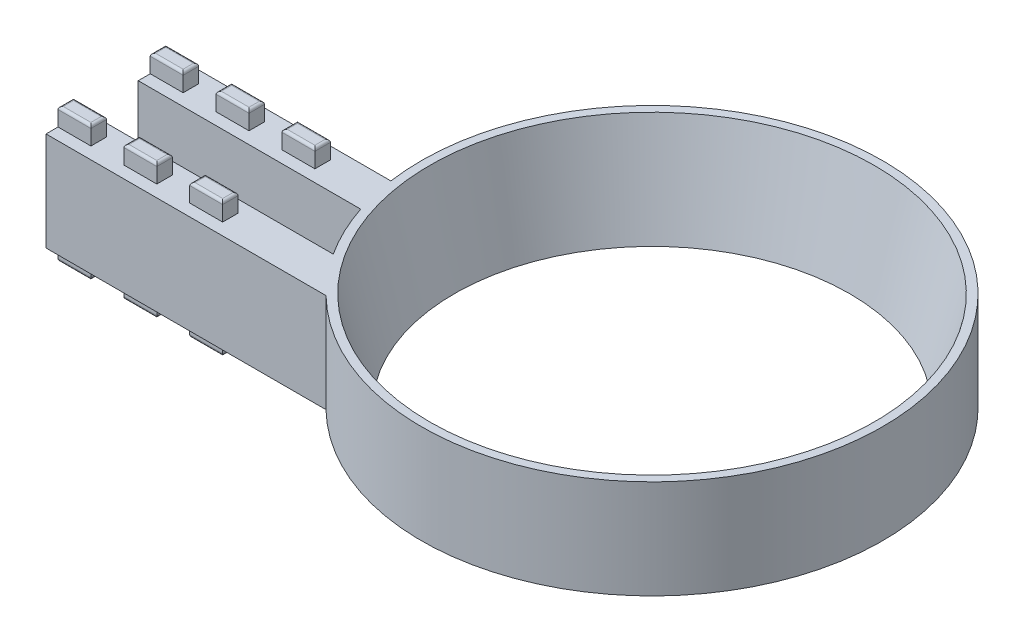
SolidWorks part; units mm, degrees
ref_plane "Front Plane" through (0, 0, 0) normal (0, 0, 1) x (1, 0, 0)
ref_plane "Top Plane" through (0, 0, 0) normal (0, 1, 0) x (1, 0, 0)
ref_plane "Right Plane" through (0, 0, 0) normal (1, 0, 0) x (0, 0, -1)
sketch "Sketch1" plane through (0, 0, 0) normal (0, 1, 0) x (1, 0, 0)
  line L0 (0, 0) -> (-44.45, 0) construction
  circle A0 centre (0, 0) radius 44.45
  dimension "D1" = 88.9
extrude "Boss-Extrude1" add sketch "Sketch1" along normal blind 19.05 contours A0
sketch "Sketch3" plane through (0, 0, 0) normal (0, -1, 0) x (1, 0, 0)
  line L0 (0, 0) -> (-44.45, 0) construction
  line L1 (-31.1085, 31.75) -> (-85.09, 31.75)
  line L2 (-85.09, 31.75) -> (-85.09, 6.35)
  line L3 (-85.09, 6.35) -> (-43.9941, 6.35)
  circle A0 centre (0, 0) radius 44.45 construction
  arc A1 (-43.9941, 6.35) -> (-31.1085, 31.75) centre (0, 0) cw
  dimension "D1" = 25.4
  dimension "D2" = 40.64
  dimension "D3" = 31.75
extrude "Boss-Extrude2" add sketch "Sketch3" against normal blind 3.175 contours L3 A1 L1 L2
sketch "Sketch4" plane through (0, 0, 31.75) normal (0, 0, 1) x (1, 0, 0)
  line L0 (-85.09, 3.175) -> (-85.09, 19.05)
  line L1 (-85.09, 19.05) -> (-31.1085, 19.05)
  line L2 (44.45, 19.05) -> (-44.45, 19.05) construction
  line L3 (-31.1085, 19.05) -> (-31.1085, 3.175)
  line L4 (-31.1085, 3.175) -> (-85.09, 3.175) construction
  line L5 (-31.1085, 3.175) -> (-85.09, 3.175)
  line L6 (-31.1085, 3.175) -> (-43.9941, 3.175) construction
  line L7 (-31.1085, 3.175) -> (-31.1085, 0) construction
sketch "Sketch5" plane through (0, 0, 6.35) normal (0, 0, -1) x (-1, 0, 0)
  line L0 (85.09, 3.175) -> (85.09, 19.05)
  line L1 (85.09, 19.05) -> (31.1085, 19.05)
  line L2 (31.1085, 19.05) -> (31.1085, 3.175)
  line L3 (31.1085, 3.175) -> (85.09, 3.175)
  line L4 (44.45, 19.05) -> (-44.45, 19.05) construction
extrude "Boss-Extrude3" add sketch "Sketch4" against normal blind 7.62
extrude "Boss-Extrude4" add sketch "Sketch5" against normal blind 7.62
sketch "Sketch2" plane through (0, 0, 0) normal (0, -1, 0) x (1, 0, 0)
  circle A0 centre (0, 0) radius 38.1
  dimension "D1" = 76.2
extrude "Cut-Extrude1" cut sketch "Sketch2" against normal through all draft 14 draft outward yes
ref_plane "Plane1" through (0, 0, 19.05) normal (0, 0, 1) x (1, 0, 0)
ref_plane "Plane2" through (0, 9.525, 0) normal (0, 1, 0) x (1, 0, 0)
sketch "Sketch6" plane through (0, 19.05, 0) normal (0, 1, 0) x (1, 0, 0)
  line L0 (-85.09, -24.13) -> (-85.09, -31.75) construction
  line L1 (-85.09, -29.4386) -> (-78.74, -29.4386)
  line L2 (-85.09, -29.4386) -> (-85.09, -26.4414)
  line L3 (-85.09, -26.4414) -> (-78.74, -26.4414)
  line L4 (-78.74, -29.4386) -> (-78.74, -26.4414)
  line L5 (-72.39, -29.4386) -> (-72.39, -26.4414)
  line L6 (-72.39, -29.4386) -> (-66.04, -29.4386)
  line L7 (-66.04, -29.4386) -> (-66.04, -26.4414)
  line L8 (-72.39, -26.4414) -> (-66.04, -26.4414)
  line L9 (-59.69, -29.4386) -> (-59.69, -26.4414)
  line L10 (-59.69, -29.4386) -> (-53.34, -29.4386)
  line L11 (-53.34, -29.4386) -> (-53.34, -26.4414)
  line L12 (-59.69, -26.4414) -> (-53.34, -26.4414)
  line L13 (-8.7312, -19.05) -> (8.7312, -19.05) construction
  line L14 (-59.69, -8.6614) -> (-53.34, -8.6614)
  line L15 (-53.34, -8.6614) -> (-53.34, -11.6586)
  line L16 (-59.69, -11.6586) -> (-53.34, -11.6586)
  line L17 (-59.69, -8.6614) -> (-59.69, -11.6586)
  line L18 (-72.39, -8.6614) -> (-66.04, -8.6614)
  line L19 (-66.04, -8.6614) -> (-66.04, -11.6586)
  line L20 (-72.39, -11.6586) -> (-66.04, -11.6586)
  line L21 (-72.39, -8.6614) -> (-72.39, -11.6586)
  line L22 (-85.09, -11.6586) -> (-78.74, -11.6586)
  line L23 (-78.74, -8.6614) -> (-78.74, -11.6586)
  line L24 (-85.09, -8.6614) -> (-78.74, -8.6614)
  line L25 (-85.09, -8.6614) -> (-85.09, -11.6586)
  point P6 (-85.09, -27.94)
  point P7 (-85.09, -27.94)
  dimension "D1" = 2.9972
  dimension "D2" = 6.35
  dimension "D3" = 3
  dimension "D4" = 6.35
extrude "Boss-Extrude5" add sketch "Sketch6" along normal blind 3.429
fillet "Fillet1" radius 0.508 24 edges at (-81.915, 22.479, 8.6614) (-78.74, 22.479, 10.16) (-81.915, 22.479, 11.6586) (-85.09, 22.479, 10.16) (-69.215, 22.479, 8.6614) (-66.04, 22.479, 10.16) (-69.215, 22.479, 11.6586) (-72.39, 22.479, 10.16) (-56.515, 22.479, 8.6614) (-53.34, 22.479, 10.16) (-56.515, 22.479, 11.6586) (-59.69, 22.479, 10.16) (-59.69, 22.479, 27.94) (-56.515, 22.479, 26.4414) (-53.34, 22.479, 27.94) (-56.515, 22.479, 29.4386) (-72.39, 22.479, 27.94) (-69.215, 22.479, 26.4414) (-66.04, 22.479, 27.94) (-69.215, 22.479, 29.4386) (-81.915, 22.479, 26.4414) (-78.74, 22.479, 27.94) (-81.915, 22.479, 29.4386) (-85.09, 22.479, 27.94)
mirror "Mirror1" about plane through (0, 9.525, 0) normal (0, 1, 0) of "Fillet1", "Boss-Extrude5"
ref_plane "Plane3" through (0, 0, -50.8) normal (0, 0, 1) x (1, 0, 0)
